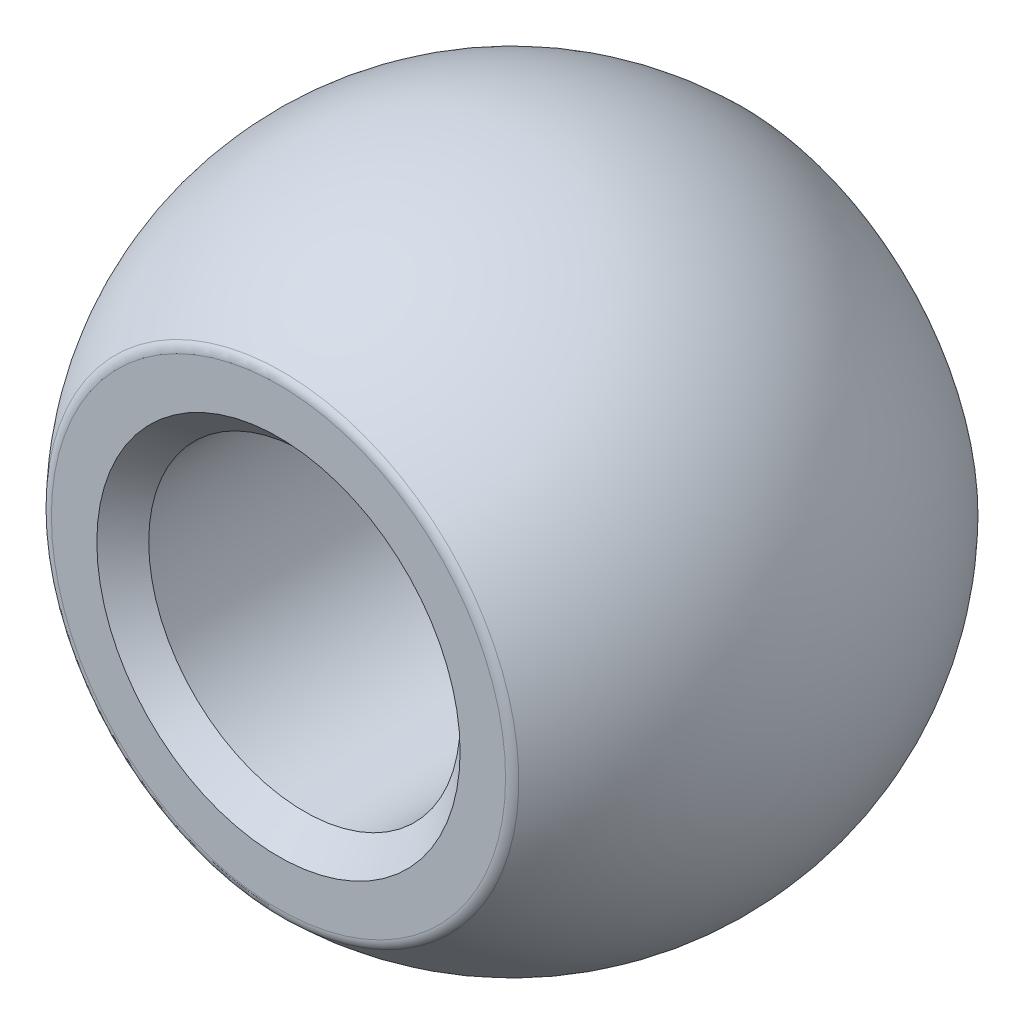
SolidWorks part; units mm, degrees
ref_plane "Alzado" through (0, 0, 0) normal (0, 0, 1) x (1, 0, 0)
ref_plane "Planta" through (0, 0, 0) normal (0, 1, 0) x (1, 0, 0)
ref_plane "Vista lateral" through (0, 0, 0) normal (1, 0, 0) x (0, 0, -1)
sketch "Croquis1" plane through (0, 0, 0) normal (0, 0, 1) x (1, 0, 0)
  line L0 (0, 6.35) -> (0, -6.35)
  arc A0 (0, 6.35) -> (0, -6.35) centre (0, 0) ccw
  point P4 (0, 0)
  dimension "D1" = 12.7
revolve "Revolución1" add sketch "Croquis1" angle 360 about L0
sketch "Croquis2" plane through (0, 0, 0) normal (0, 0, 1) x (1, 0, 0)
  circle A0 centre (0, 0) radius 3
  dimension "D1" = 6
extrude "Cortar-Extruir1" cut sketch "Croquis2" against normal through all both and the other way through all
sketch "Croquis3" plane through (0, 0, 0) normal (1, 0, 0) x (0, 0, -1)
  line L0 (-5.5967, 0) -> (0, 0) construction
  line L1 (-5.5967, -3) -> (-5.5967, 3) construction
  line L2 (0, 0) -> (0, 6.35) construction
  line L3 (4.5, 6.35) -> (5.5967, 6.35)
  line L4 (-4.5, -6.35) -> (-5.5967, -6.35)
  line L5 (-4.5, -6.35) -> (-4.5, 6.35)
  line L6 (-4.5, 6.35) -> (-5.5967, 6.35)
  line L7 (-5.5967, -6.35) -> (-5.5967, 6.35)
  line L8 (-4.5, -6.35) -> (-5.5967, 6.35) construction
  line L9 (-4.5, 6.35) -> (-5.5967, -6.35) construction
  line L10 (5.5967, -6.35) -> (5.5967, 6.35)
  line L11 (4.5, -6.35) -> (5.5967, -6.35)
  line L12 (4.5, -6.35) -> (4.5, 6.35)
  arc A0 (5.5967, 3) -> (-5.5967, 3) centre (0, 0) ccw construction
  point P9 (-5.0483, 0)
  dimension "D1" = 12.7
  dimension "D2" = 4.5
extrude "Cortar-Extruir2" cut sketch "Croquis3" against normal through all both and the other way through all
fillet "Redondeo1" radius 0.25 2 edges at (-4.4802, 0, 4.5) (4.4802, 0, -4.5)
chamfer "Chaflán1" distance 0.5 angle 45 2 edges at (-3, 0, 4.5) (3, 0, -4.5)
